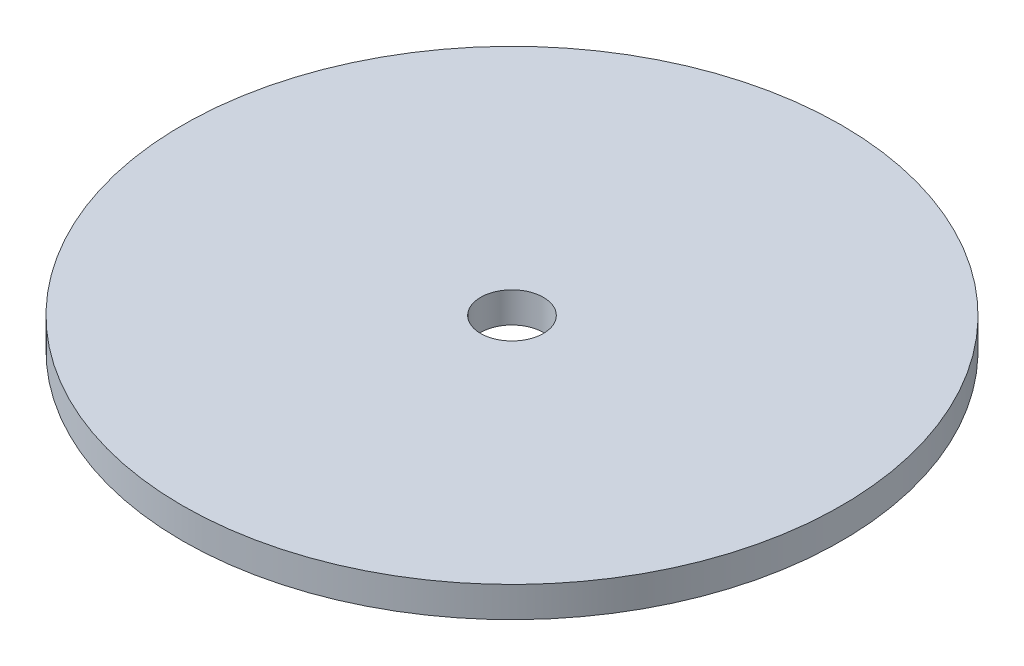
SolidWorks part; units mm, degrees
material "Fiberglass (correct density)"
ref_plane "Front Plane" through (0, 0, 0) normal (0, 0, 1) x (1, 0, 0)
ref_plane "Top Plane" through (0, 0, 0) normal (0, 1, 0) x (1, 0, 0)
ref_plane "Right Plane" through (0, 0, 0) normal (1, 0, 0) x (0, 0, -1)
sketch "Sketch1" plane through (0, 0, 0) normal (0, 1, 0) x (1, 0, 0)
  circle A0 centre (0, 0) radius 34.29
  dimension "D1" = 68.58
extrude "Boss-Extrude1" add sketch "Sketch1" along normal blind 3.175
sketch "Sketch2" plane through (0, 3.175, 0) normal (0, 1, 0) x (1, 0, 0)
  point P0 (0, 0)
hole_wizard "1/4 Clearance Hole1" positions "Sketch3" profile "Sketch5" hole size "1/4" standard "ANSI Inch" end condition up to next
sketch "Sketch3" plane through (0, 3.175, 0) normal (0, 1, 0) x (1, 0, 0)
  point P0 (0, 0)
sketch "Sketch5" plane through (0, 3.175, 0) normal (1, 0, 0) x (0, 0, 1)
  line L0 (0, 0) -> (0, 3.175)
  line L1 (0, 3.175) -> (3.2639, 3.175)
  line L2 (3.2639, 3.175) -> (3.2639, 0)
  line L5 (3.2639, 0) -> (0, 0)
  line L11 (0, -6.35) -> (0, 107.95) construction
  dimension "Thru Hole Dia." = 6.5278
  dimension "Thru Hole Depth" = 3.175
